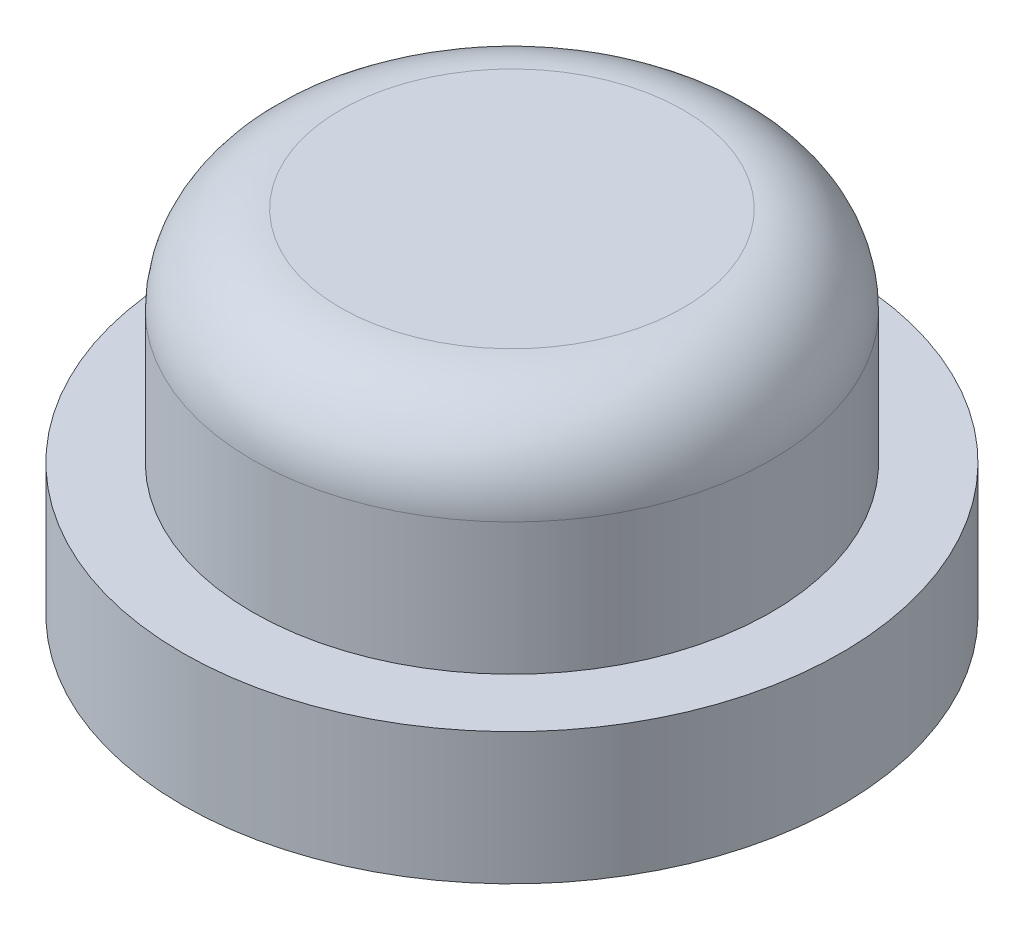
SolidWorks part; units mm, degrees
ref_plane "前视基准面" through (0, 0, 0) normal (0, 0, 1) x (1, 0, 0)
ref_plane "上视基准面" through (0, 0, 0) normal (0, 1, 0) x (1, 0, 0)
ref_plane "右视基准面" through (0, 0, 0) normal (1, 0, 0) x (0, 0, -1)
other "Configuration Table"
sketch "草图1" plane through (0, 0, 0) normal (0, 1, 0) x (1, 0, 0)
  circle A0 centre (0, 0) radius 3.75
  dimension "D1" = 7.5
extrude "凸台-拉伸1" add sketch "草图1" along normal blind 1.5
sketch "草图2" plane through (0, 1.5, 0) normal (0, 1, 0) x (1, 0, 0)
  circle A0 centre (0, 0) radius 2.95
  dimension "D1" = 5.9
extrude "凸台-拉伸2" add sketch "草图2" along normal blind 2.5
fillet "圆角1" radius 1 1 edges at (0, 4, 2.95)
